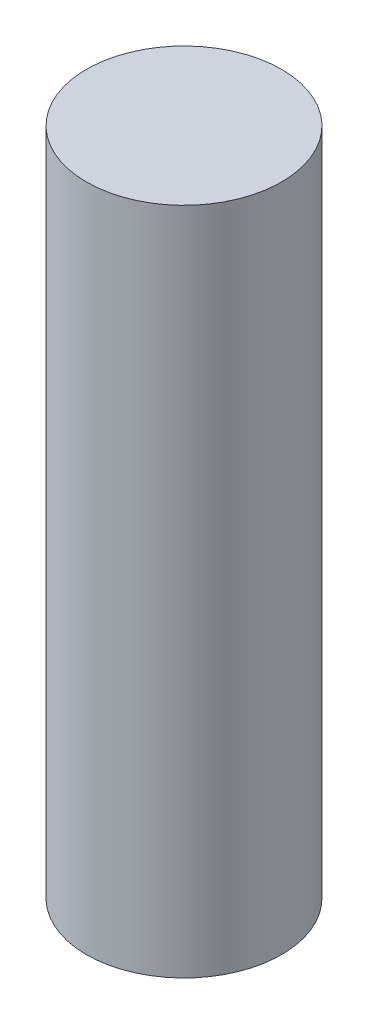
SolidWorks part; units mm, degrees
ref_plane "Front Plane" through (0, 0, 0) normal (0, 0, 1) x (1, 0, 0)
ref_plane "Top Plane" through (0, 0, 0) normal (0, 1, 0) x (1, 0, 0)
ref_plane "Right Plane" through (0, 0, 0) normal (1, 0, 0) x (0, 0, -1)
sketch "Sketch1" plane through (0, 0, 0) normal (0, 1, 0) x (1, 0, 0)
  circle A0 centre (0, 0) radius 3.5
  dimension "D1" = 7
extrude "Boss-Extrude1" add sketch "Sketch1" along normal blind 24
